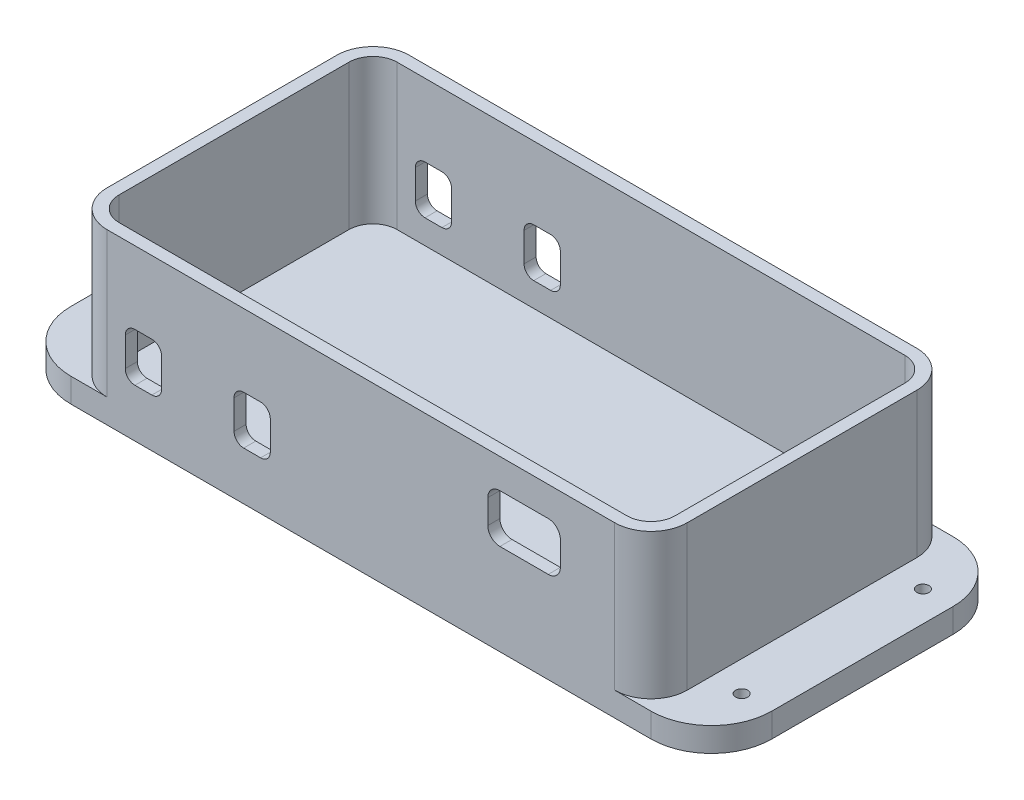
SolidWorks part; units mm, degrees
ref_plane "Front Plane" through (0, 0, 0) normal (0, 0, 1) x (1, 0, 0)
ref_plane "Top Plane" through (0, 0, 0) normal (0, 1, 0) x (1, 0, 0)
ref_plane "Right Plane" through (0, 0, 0) normal (1, 0, 0) x (0, 0, -1)
sketch "Sketch1" plane through (0, 0, 0) normal (0, 1, 0) x (1, 0, 0)
  line L1 (0, 0) -> (147.32, 0)
  line L2 (0, 0) -> (0, 63.5)
  line L3 (0, 63.5) -> (147.32, 63.5)
  line L4 (147.32, 0) -> (147.32, 63.5)
  dimension "D1" = 147.32
  dimension "D2" = 63.5
extrude "Boss-Extrude3" add sketch "Sketch1" along normal blind 5.08
fillet "Fillet4" radius 12.7 4 edges at (147.32, 2.54, -63.5) (147.32, 2.54, 0) (0, 2.54, 0) (0, 2.54, -63.5)
sketch "Sketch4" plane through (0, 5.08, 0) normal (0, 1, 0) x (1, 0, 0)
  line L1 (12.7, 63.5) -> (134.62, 63.5)
  line L2 (12.7, 63.5) -> (12.7, 0)
  line L3 (12.7, 0) -> (134.62, 0)
  line L4 (134.62, 63.5) -> (134.62, 0)
  line L5 (15.24, 60.96) -> (132.08, 60.96)
  line L6 (15.24, 60.96) -> (15.24, 2.54)
  line L7 (15.24, 2.54) -> (132.08, 2.54)
  line L8 (132.08, 60.96) -> (132.08, 2.54)
  dimension "D1" = 2.54
  dimension "D2" = 2.54
  dimension "D3" = 2.54
  dimension "D4" = 2.54
extrude "Boss-Extrude4" add sketch "Sketch4" along normal blind 30.48
sketch "Sketch9" plane through (0, 5.08, 0) normal (0, 1, 0) x (1, 0, 0)
  line L0 (73.66, 60.96) -> (73.66, 2.54) construction
  line L1 (15.24, 60.96) -> (25.4, 60.96)
  line L2 (15.24, 60.96) -> (15.24, 50.8)
  line L3 (15.24, 50.8) -> (25.4, 50.8)
  line L4 (25.4, 60.96) -> (25.4, 50.8)
  line L5 (132.08, 60.96) -> (15.24, 60.96) construction
  line L6 (15.24, 2.54) -> (132.08, 2.54) construction
  line L7 (15.24, 31.75) -> (132.08, 31.75) construction
  line L8 (15.24, 60.96) -> (15.24, 2.54) construction
  line L9 (132.08, 2.54) -> (132.08, 60.96) construction
  line L10 (121.92, 60.96) -> (121.92, 50.8)
  line L11 (132.08, 50.8) -> (121.92, 50.8)
  line L12 (132.08, 60.96) -> (132.08, 50.8)
  line L13 (132.08, 60.96) -> (121.92, 60.96)
  line L14 (132.08, 2.54) -> (121.92, 2.54)
  line L15 (132.08, 2.54) -> (132.08, 12.7)
  line L16 (132.08, 12.7) -> (121.92, 12.7)
  line L17 (121.92, 2.54) -> (121.92, 12.7)
  line L18 (25.4, 2.54) -> (25.4, 12.7)
  line L19 (15.24, 12.7) -> (25.4, 12.7)
  line L20 (15.24, 2.54) -> (15.24, 12.7)
  line L21 (15.24, 2.54) -> (25.4, 2.54)
  dimension "D1" = 10.16
  dimension "D2" = 10.16
extrude "Boss-Extrude5" add sketch "Sketch9" along normal blind 5.08
fillet "Fillet9" radius 5.08 4 edges at (121.92, 7.62, -12.7) (25.4, 7.62, -12.7) (121.92, 7.62, -50.8) (25.4, 7.62, -50.8)
sketch "Sketch10" plane through (0, 10.16, 0) normal (0, 1, 0) x (1, 0, 0)
  circle A0 centre (20.32, 55.88) radius 3.175
  circle A1 centre (127, 55.88) radius 3.175
  circle A2 centre (20.32, 7.62) radius 3.175
  circle A3 centre (127, 7.62) radius 3.175
  dimension "D1" = 6.35
  dimension "D2" = 6.35
  dimension "D3" = 6.35
  dimension "D4" = 6.35
extrude "Cut-Extrude7" cut sketch "Sketch10" against normal through all
sketch "Sketch11" plane through (0, 10.16, 0) normal (0, 1, 0) x (1, 0, 0)
  circle A0 centre (20.32, 55.88) radius 3.175
  circle A1 centre (20.32, 55.88) radius 1.27
  circle A2 centre (127, 55.88) radius 3.175
  circle A3 centre (127, 55.88) radius 1.27
  circle A4 centre (20.32, 7.62) radius 3.175
  circle A5 centre (20.32, 7.62) radius 1.27
  circle A6 centre (127, 7.62) radius 3.175
  circle A7 centre (127, 7.62) radius 1.27
  dimension "D1" = 6.35
  dimension "D2" = 2.54
  dimension "D3" = 6.35
  dimension "D4" = 2.54
  dimension "D5" = 6.35
  dimension "D6" = 2.54
  dimension "D7" = 6.35
  dimension "D8" = 2.54
fillet "Fillet12" radius 7.62 4 edges at (134.62, 20.32, 0) (134.62, 20.32, -63.5) (12.7, 20.32, -63.5) (12.7, 20.32, 0)
sketch "Sketch12" plane through (0, 0, 0) normal (0, 0, 1) x (1, 0, 0)
  line L0 (107.95, 19.177) -> (107.95, 29.337) construction
  line L1 (100.33, 19.177) -> (115.57, 19.177)
  line L2 (100.33, 19.177) -> (100.33, 29.337)
  line L3 (100.33, 29.337) -> (115.57, 29.337)
  line L4 (115.57, 19.177) -> (115.57, 29.337)
  line L5 (100.33, 24.257) -> (115.57, 24.257) construction
  dimension "D1" = 19.05
  dimension "D2" = 15.24
  dimension "D3" = 10.16
  dimension "D4" = 19.177
sketch "Sketch13" plane through (0, 0, 0) normal (0, 0, 1) x (1, 0, 0)
  line L0 (27.94, 20.32) -> (27.94, 10.16) construction
  line L1 (24.13, 20.32) -> (31.75, 20.32)
  line L2 (24.13, 20.32) -> (24.13, 10.16)
  line L3 (24.13, 10.16) -> (31.75, 10.16)
  line L4 (31.75, 20.32) -> (31.75, 10.16)
  line L5 (46.99, 20.32) -> (54.61, 20.32)
  line L6 (46.99, 20.32) -> (46.99, 10.16)
  line L7 (46.99, 10.16) -> (54.61, 10.16)
  line L8 (54.61, 20.32) -> (54.61, 10.16)
  line L9 (50.8, 20.32) -> (50.8, 10.16) construction
  dimension "D1" = 5.08
  dimension "D2" = 10.16
  dimension "D3" = 7.62
  dimension "D4" = 30.48
  dimension "D5" = 7.62
  dimension "D6" = 7.62
extrude "Boss-Extrude7" add sketch "Sketch11" against normal blind 5.08
sketch "Sketch15" plane through (0, 5.08, 0) normal (0, 1, 0) x (1, 0, 0)
  line L0 (73.66, 60.96) -> (73.66, 2.54) construction
  line L1 (121.92, 60.96) -> (25.4, 60.96) construction
  line L2 (25.4, 2.54) -> (121.92, 2.54) construction
  circle A0 centre (6.35, 50.8) radius 1.27
  circle A1 centre (6.35, 12.7) radius 1.27
  circle A3 centre (140.97, 12.7) radius 1.27
  circle A4 centre (140.97, 50.8) radius 1.27
  dimension "D1" = 6.35
  dimension "D2" = 2.54
  dimension "D3" = 2.54
extrude "Cut-Extrude10" cut sketch "Sketch15" against normal blind 2.54
sketch "Sketch16" plane through (0, 0, 0) normal (0, -1, 0) x (1, 0, 0)
  circle A0 centre (20.32, -7.62) radius 3.175
  circle A1 centre (127, -7.62) radius 3.175
  circle A2 centre (20.32, -55.88) radius 3.175
  circle A3 centre (127, -55.88) radius 3.175
extrude "Boss-Extrude9" add sketch "Sketch16" against normal blind 2.54
sketch "Sketch17" plane through (0, 10.16, 0) normal (0, 1, 0) x (1, 0, 0)
  line L1 (15.24, 60.96) -> (132.08, 60.96)
  line L2 (15.24, 60.96) -> (15.24, 2.54)
  line L3 (15.24, 2.54) -> (132.08, 2.54)
  line L4 (132.08, 60.96) -> (132.08, 2.54)
extrude "Cut-Extrude11" cut sketch "Sketch17" against normal blind 5.08
sketch "Sketch18" plane through (0, 5.08, 0) normal (0, 1, 0) x (1, 0, 0)
  line L1 (15.24, 60.96) -> (132.08, 60.96)
  line L2 (15.24, 60.96) -> (15.24, 2.54)
  line L3 (15.24, 2.54) -> (132.08, 2.54)
  line L4 (132.08, 60.96) -> (132.08, 2.54)
extrude "Boss-Extrude10" add sketch "Sketch18" against normal blind 5.08
fillet "Fillet16" radius 5.08 4 edges at (132.08, 20.32, -2.54) (15.24, 20.32, -2.54) (132.08, 20.32, -60.96) (15.24, 20.32, -60.96)
extrude "Cut-Extrude12" cut sketch "Sketch13" against normal through all
fillet "Fillet17" radius 2.032 16 edges at (24.13, 10.16, -62.23) (46.99, 10.16, -62.23) (31.75, 20.32, -62.23) (54.61, 20.32, -62.23) (31.75, 10.16, -62.23) (54.61, 10.16, -62.23) (24.13, 20.32, -62.23) (46.99, 20.32, -62.23) (46.99, 10.16, -1.27) (24.13, 10.16, -1.27) (54.61, 20.32, -1.27) (31.75, 20.32, -1.27) (46.99, 20.32, -1.27) (24.13, 20.32, -1.27) (54.61, 10.16, -1.27) (31.75, 10.16, -1.27)
extrude "Cut-Extrude14" cut sketch "Sketch12" against normal up to next
fillet "Fillet18" radius 2.54 4 edges at (100.33, 19.177, -1.27) (100.33, 29.337, -1.27) (115.57, 29.337, -1.27) (115.57, 19.177, -1.27)
